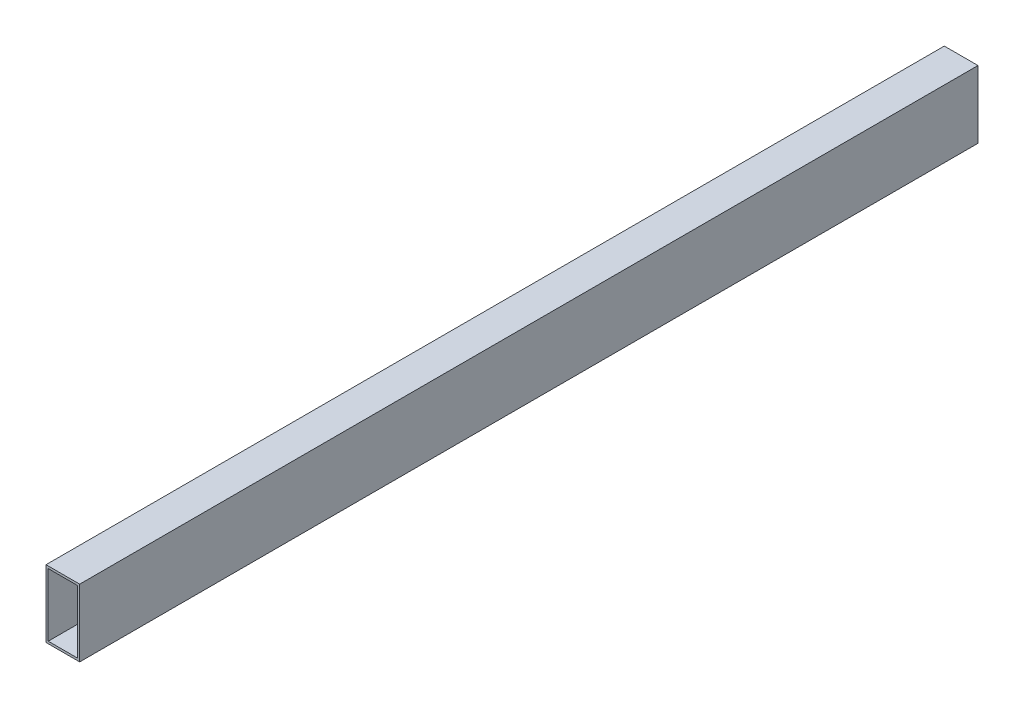
SolidWorks part; units mm, degrees
ref_plane "Спереди" through (0, 0, 0) normal (0, 0, 1) x (1, 0, 0)
ref_plane "Сверху" through (0, 0, 0) normal (0, 1, 0) x (1, 0, 0)
ref_plane "Справа" through (0, 0, 0) normal (1, 0, 0) x (0, 0, -1)
sketch "Эскиз1" plane through (0, 0, 0) normal (0, 0, 1) x (1, 0, 0)
  line L1 (-48.5553, 33.7895) -> (-18.5553, 33.7895)
  line L2 (-48.5553, 33.7895) -> (-48.5553, -26.2105)
  line L3 (-48.5553, -26.2105) -> (-18.5553, -26.2105)
  line L4 (-18.5553, 33.7895) -> (-18.5553, -26.2105)
  line L5 (-46.5553, 31.7895) -> (-20.5553, 31.7895)
  line L6 (-46.5553, 31.7895) -> (-46.5553, -24.2105)
  line L7 (-46.5553, -24.2105) -> (-20.5553, -24.2105)
  line L8 (-20.5553, 31.7895) -> (-20.5553, -24.2105)
  dimension "D1" = 30
  dimension "D2" = 60
  dimension "D3" = 2
  dimension "D4" = 2
  dimension "D5" = 2
  dimension "D6" = 2
extrude "Бобышка-Вытянуть1" add sketch "Эскиз1" along normal blind 800
